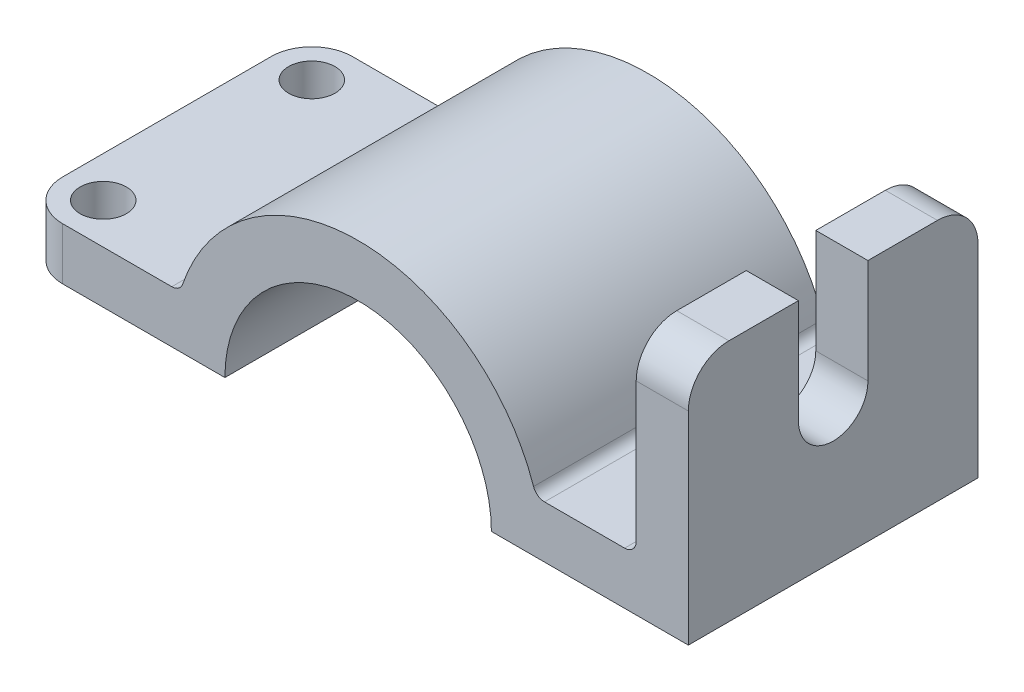
SolidWorks part; units mm, degrees
ref_plane "Front Plane" through (0, 0, 0) normal (0, 0, 1) x (1, 0, 0)
ref_plane "Top Plane" through (0, 0, 0) normal (0, 1, 0) x (1, 0, 0)
ref_plane "Right Plane" through (0, 0, 0) normal (1, 0, 0) x (0, 0, -1)
sketch "Sketch2" plane through (0, 0, 0) normal (0, 0, 1) x (1, 0, 0)
  line L0 (23, 0) -> (57, 0)
  line L1 (57, 0) -> (57, 42)
  line L2 (57, 42) -> (48, 42)
  line L3 (48, 42) -> (48, 11)
  line L4 (46, 9) -> (32.1714, 9)
  line L5 (-23, 0) -> (-58, 0)
  line L6 (-58, 0) -> (-58, 9)
  line L7 (-58, 9) -> (-32.1714, 9)
  arc A0 (-23, 0) -> (23, 0) centre (0, 0) cw
  arc A1 (-30.279, 10.3529) -> (30.279, 10.3529) centre (0, 0) cw
  arc A2 (48, 11) -> (46, 9) centre (46, 11) cw
  arc A3 (32.1714, 9) -> (30.279, 10.3529) centre (32.1714, 11) cw
  arc A4 (-32.1714, 9) -> (-30.279, 10.3529) centre (-32.1714, 11) ccw
  point P14 (0, 0)
  point P15 (0, 0)
  point P16 (48, 9)
  dimension "D1" = 23
  dimension "D2" = 32
  dimension "D8" = 2
  dimension "D3" = 9
  dimension "D4" = 9
  dimension "D5" = 57
  dimension "D6" = 115
  dimension "D7" = 42
extrude "Boss-Extrude1" add sketch "Sketch2" along normal mid plane 50
sketch "Sketch3" plane through (57, 0, 0) normal (1, 0, 0) x (0, 0, -1)
  line L0 (-6, 24) -> (-6, 42)
  line L1 (-25, 42) -> (25, 42) construction
  line L2 (6, 24) -> (6, 42)
  line L3 (-6, 42) -> (6, 42)
  arc A0 (-6, 24) -> (6, 24) centre (0, 24) ccw
  point P8 (0, 0)
  dimension "D1" = 12
  dimension "D2" = 18
extrude "Cut-Extrude1" cut sketch "Sketch3" against normal up to surface (9 mm away) up to face at (48, 26.5, 0)
fillet "Fillet1" radius 7 4 edges at (-58, 4.5, 25) (-58, 4.5, -25) (52.5, 42, -25) (52.5, 42, 25)
sketch "Sketch4" plane through (0, 9, 0) normal (0, 1, 0) x (1, 0, 0)
  line L0 (-58, -18) -> (-51, -18)
  line L1 (-58, 18) -> (-51, 18)
  circle A0 centre (-51, 18) radius 4
  circle A1 centre (-51, -18) radius 4
  dimension "D1" = 8
  dimension "D2" = 8
extrude "Cut-Extrude2" cut sketch "Sketch4" against normal up to surface (9 mm away) up to face at (-44.4832, 0, 0)
